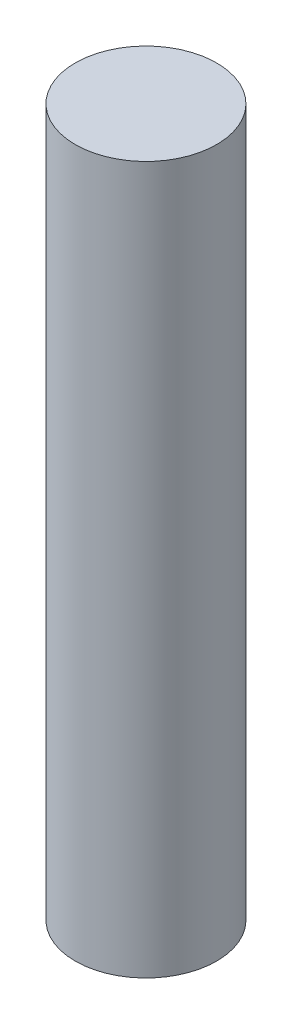
SolidWorks part; units mm, degrees
material "Brass"
ref_plane "Front Plane" through (0, 0, 0) normal (0, 0, 1) x (1, 0, 0)
ref_plane "Top Plane" through (0, 0, 0) normal (0, 1, 0) x (1, 0, 0)
ref_plane "Right Plane" through (0, 0, 0) normal (1, 0, 0) x (0, 0, -1)
sketch "Sketch1" plane through (0, 0, 0) normal (0, 1, 0) x (1, 0, 0)
  circle A0 centre (0, 0) radius 1
  dimension "D1" = 2
extrude "Boss-Extrude1" add sketch "Sketch1" along normal blind 10
scale "Scale1" scale about centroid uniform scaling yes scale factor 6
